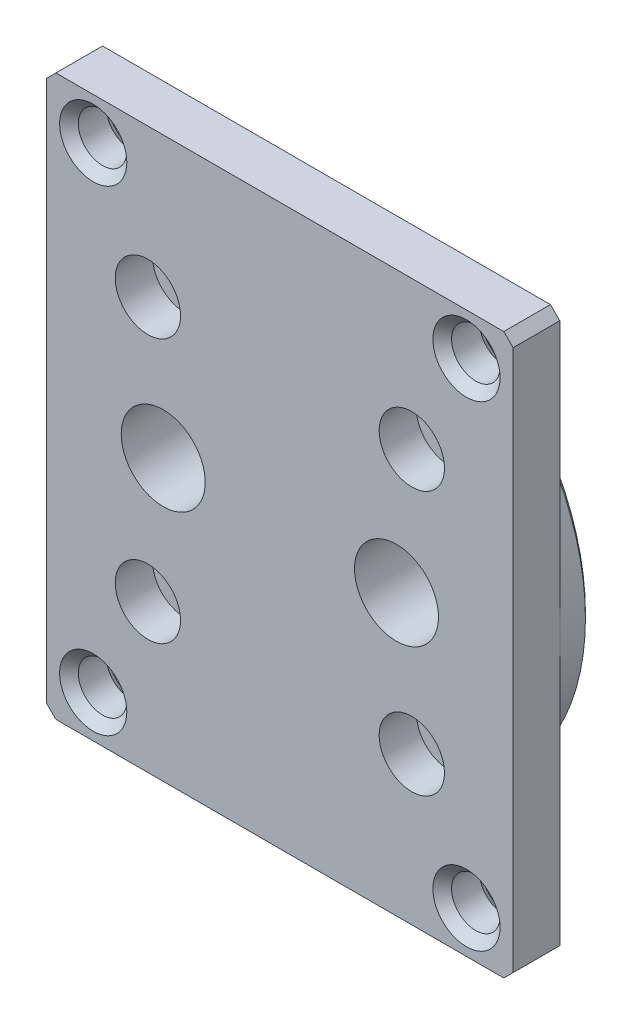
SolidWorks part; units mm, degrees
ref_plane "Front Plane" through (0, 0, 0) normal (0, 0, 1) x (1, 0, 0)
ref_plane "Top Plane" through (0, 0, 0) normal (0, 1, 0) x (1, 0, 0)
ref_plane "Right Plane" through (0, 0, 0) normal (1, 0, 0) x (0, 0, -1)
sketch "Sketch1" plane through (0, 0, 0) normal (0, 0, 1) x (1, 0, 0)
  circle A0 centre (0, 0) radius 25
  dimension "D1" = 50
extrude "Boss-Extrude1" add sketch "Sketch1" along normal blind 8.25
sketch "Sketch2" plane through (0, 0, 8.25) normal (0, 0, 1) x (1, 0, 0)
  line L1 (-25, 25) -> (25, 25)
  line L2 (-25, 25) -> (-25, -25)
  line L3 (-25, -25) -> (25, -25)
  line L4 (25, 25) -> (25, -25)
  circle A0 centre (0, 0) radius 25 construction
extrude "Boss-Extrude2" add sketch "Sketch2" against normal blind 5
sketch "Sketch3" plane through (0, 0, 0) normal (0, 0, -1) x (-1, 0, 0)
  line L0 (-25, 25) -> (0, 25) construction
  line L1 (-14.1421, -14.1421) -> (14.1421, -14.1421) construction
  line L2 (-14.1421, -14.1421) -> (-14.1421, 14.1421) construction
  line L3 (-14.1421, 14.1421) -> (14.1421, 14.1421) construction
  line L4 (14.1421, -14.1421) -> (14.1421, 14.1421) construction
  line L5 (-25, 0) -> (-25, 25) construction
  line L6 (0, -25) -> (-25, -25) construction
  line L7 (25, 25) -> (25, 0) construction
  circle A0 centre (12.5, 0) radius 4.5
  circle A1 centre (-12.5, 0) radius 4.5
  circle A2 centre (-14.1421, 14.1421) radius 1.75
  circle A3 centre (14.1421, 14.1421) radius 1.75
  circle A4 centre (14.1421, -14.1421) radius 1.75
  circle A5 centre (-14.1421, -14.1421) radius 1.75
  dimension "D1" = 9
  dimension "D2" = 9
  dimension "D3" = 3.5
  dimension "D4" = 3.5
  dimension "D5" = 3.5
  dimension "D6" = 3.5
  dimension "D7" = 10.8579
  dimension "D8" = 10.8579
  dimension "D9" = 10.8579
  dimension "D10" = 12.5
  dimension "D11" = 12.5
extrude "Cut-Extrude1" cut sketch "Sketch3" against normal through all contours A1
sketch "Sketch5" plane through (0, 0, 8.25) normal (0, 0, 1) x (1, 0, 0)
  circle A0 centre (-14.1421, 14.1421) radius 3.5
  dimension "D1" = 7
extrude "Cut-Extrude3" cut sketch "Sketch5" against normal blind 4
pattern_circular "CirPattern2" count 4 over 360 about axis through (0, 0, 0) along (0, 0, 1) of "Cut-Extrude3"
chamfer "Chamfer2" distance 0.5 angle 45 7 edges at (25, 0, 0) (-17, 0, 0) (12.3921, -14.1421, 0) (-15.8921, -14.1421, 0) (-15.8921, 14.1421, 0) (12.3921, 14.1421, 0) (8, 0, 0)
sketch "Sketch6" plane through (0, 0, 8.25) normal (0, 0, 1) x (1, 0, 0)
  line L1 (-25, 25) -> (25, 25)
  line L2 (-25, 25) -> (-25, 30)
  line L3 (-25, 30) -> (25, 30)
  line L4 (25, 25) -> (25, 30)
  line L5 (-25, -25) -> (25, -25)
  line L6 (-25, -25) -> (-25, -30)
  line L7 (-25, -30) -> (25, -30)
  line L8 (25, -25) -> (25, -30)
  point P5 (25, -25)
  dimension "D1" = 5
  dimension "D2" = 5
extrude "Boss-Extrude3" add sketch "Sketch6" against normal up to surface (5 mm away) up to face at (-18.3926, 18.3926, 3.25)
sketch "Sketch7" plane through (0, 0, 3.25) normal (0, 0, -1) x (-1, 0, 0)
  line L0 (-25, 0) -> (-25, 30) construction
  line L1 (-20, 25.5) -> (20, 25.5) construction
  line L2 (-20, 25.5) -> (-20, -25.5) construction
  line L3 (-20, -25.5) -> (20, -25.5) construction
  line L4 (20, 25.5) -> (20, -25.5) construction
  line L5 (25, 30) -> (25, 0) construction
  circle A0 centre (-20, 25.5) radius 2.6
  circle A1 centre (20, 25.5) radius 2.6
  circle A2 centre (20, -25.5) radius 2.6
  circle A3 centre (-20, -25.5) radius 2.6
  dimension "D5" = 5.2
  dimension "D6" = 5.2
  dimension "D7" = 5.2
  dimension "D8" = 5.2
  dimension "D1" = 51
  dimension "D2" = 25.5
  dimension "D3" = 5
  dimension "D4" = 5
extrude "Cut-Extrude4" cut sketch "Sketch7" against normal through all
chamfer "Chamfer3" distance 1 angle 45 12 edges at (17.4, 25.5, 3.25) (17.4, 25.5, 8.25) (-22.6, 25.5, 3.25) (-22.6, 25.5, 8.25) (-22.6, -25.5, 3.25) (-22.6, -25.5, 8.25) (17.4, -25.5, 3.25) (17.4, -25.5, 8.25) (-25, 30, 5.75) (-25, -30, 5.75) (25, -30, 5.75) (25, 30, 5.75)
